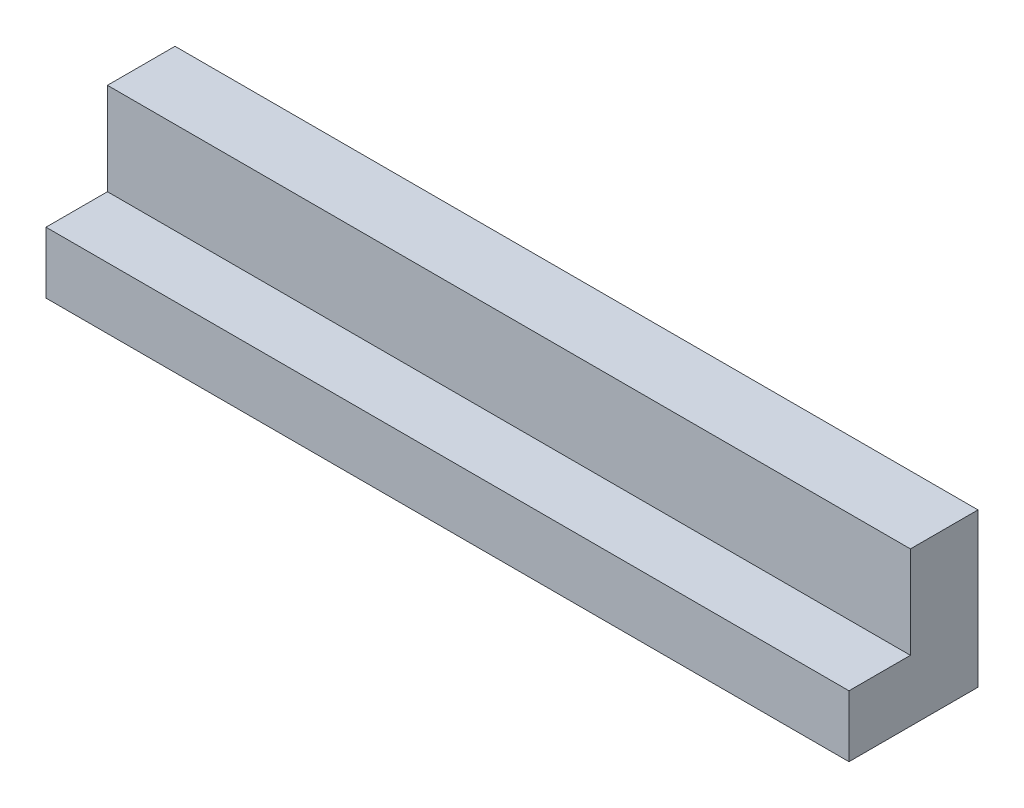
SolidWorks part; units mm, degrees
ref_plane "Plan de face" through (0, 0, 0) normal (0, 0, 1) x (1, 0, 0)
ref_plane "Plan de dessus" through (0, 0, 0) normal (0, 1, 0) x (1, 0, 0)
ref_plane "Plan de droite" through (0, 0, 0) normal (1, 0, 0) x (0, 0, -1)
sketch "Esquisse2" plane through (0, 0, 0) normal (0, 0, 1) x (1, 0, 0)
  line L0 (0, 0) -> (261.4, 0)
  line L1 (261.4, 0) -> (261.4, 50)
  line L2 (261.4, 50) -> (0, 50)
  line L3 (0, 50) -> (0, 0)
extrude "Boss.-Extru.1" add sketch "Esquisse2" along normal blind 42
sketch "Esquisse3" plane through (0, 0, 42) normal (0, 0, 1) x (1, 0, 0)
  line L0 (0, 50) -> (0, 0) construction
  line L1 (0, 20) -> (261.4, 20)
  line L2 (261.4, 0) -> (261.4, 50) construction
  line L3 (0, 0) -> (261.4, 0) construction
  dimension "D1" = 20
extrude "Enlèv. mat.-Extru.1" cut sketch "Esquisse3" against normal blind 20 and the other way through all
